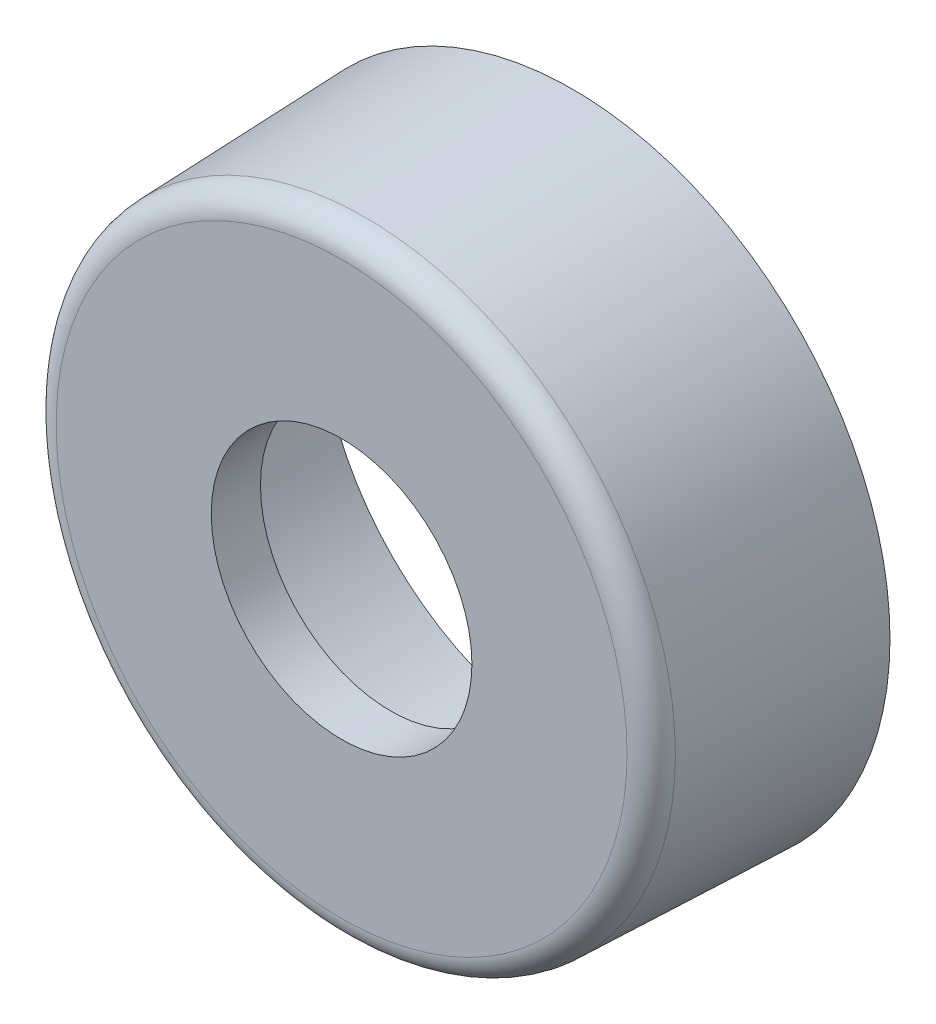
SolidWorks part; units mm, degrees
ref_plane "Plan de face" through (0, 0, 0) normal (0, 0, 1) x (1, 0, 0)
ref_plane "Plan de dessus" through (0, 0, 0) normal (0, 1, 0) x (1, 0, 0)
ref_plane "Plan de droite" through (0, 0, 0) normal (1, 0, 0) x (0, 0, -1)
sketch "Esquisse1" plane through (0, 0, 0) normal (0, 0, 1) x (1, 0, 0)
  circle A0 centre (0, 0) radius 6.45
  circle A1 centre (0, 0) radius 5.15
  dimension "D1" = 12.9
  dimension "D2" = 10.3
extrude "Boss.-Extru.1" add sketch "Esquisse1" along normal blind 4.7 draft 2
sketch "Esquisse2" plane through (0, 0, 4.7) normal (0, 0, 1) x (1, 0, 0)
  circle A0 centre (0, 0) radius 6.2859
  circle A1 centre (0, 0) radius 2.65
  dimension "D1" = 5.3
extrude "Boss.-Extru.2" add sketch "Esquisse2" against normal blind 1
fillet "Congé1" radius 0.5 1 edges at (6.2859, 0, 4.7)
